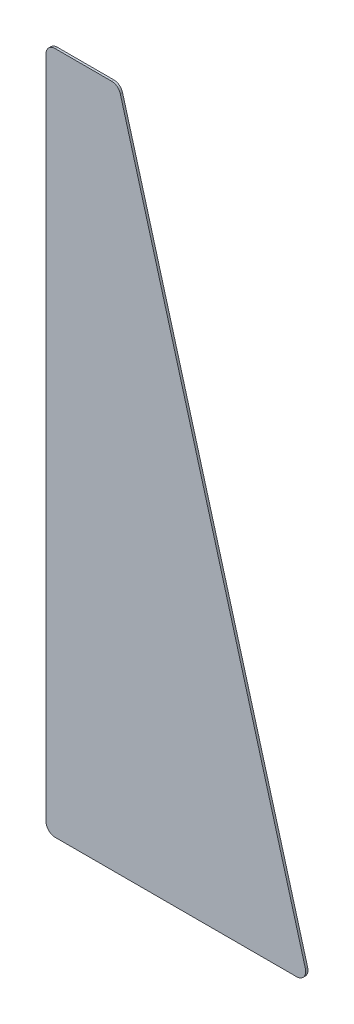
SolidWorks part; units mm, degrees
material "PC High Viscosity"
ref_plane "Front Plane" through (0, 0, 0) normal (0, 0, 1) x (1, 0, 0)
ref_plane "Top Plane" through (0, 0, 0) normal (0, 1, 0) x (1, 0, 0)
ref_plane "Right Plane" through (0, 0, 0) normal (1, 0, 0) x (0, 0, -1)
sketch "Sketch2" plane through (0, 0, 0) normal (0, 0, 1) x (1, 0, 0)
  line L0 (0, 0) -> (0, 479.171)
  line L5 (184.15, 0) -> (0, 0)
  line L6 (0, 479.171) -> (50.8, 479.171)
  line L7 (50.8, 479.171) -> (184.15, 0)
  point P3 (177.5556, 0)
  dimension "D1" = 479.171
  dimension "D2" = 184.15
  dimension "D5" = 50.8
extrude "Boss-Extrude1" add sketch "Sketch2" along normal blind 1.5875
fillet "Fillet1" radius 6.35 4 edges at (0, 0, 0.7937) (50.8, 479.171, 0.7937) (0, 479.171, 0.7937) (184.15, 0, 0.7937)
